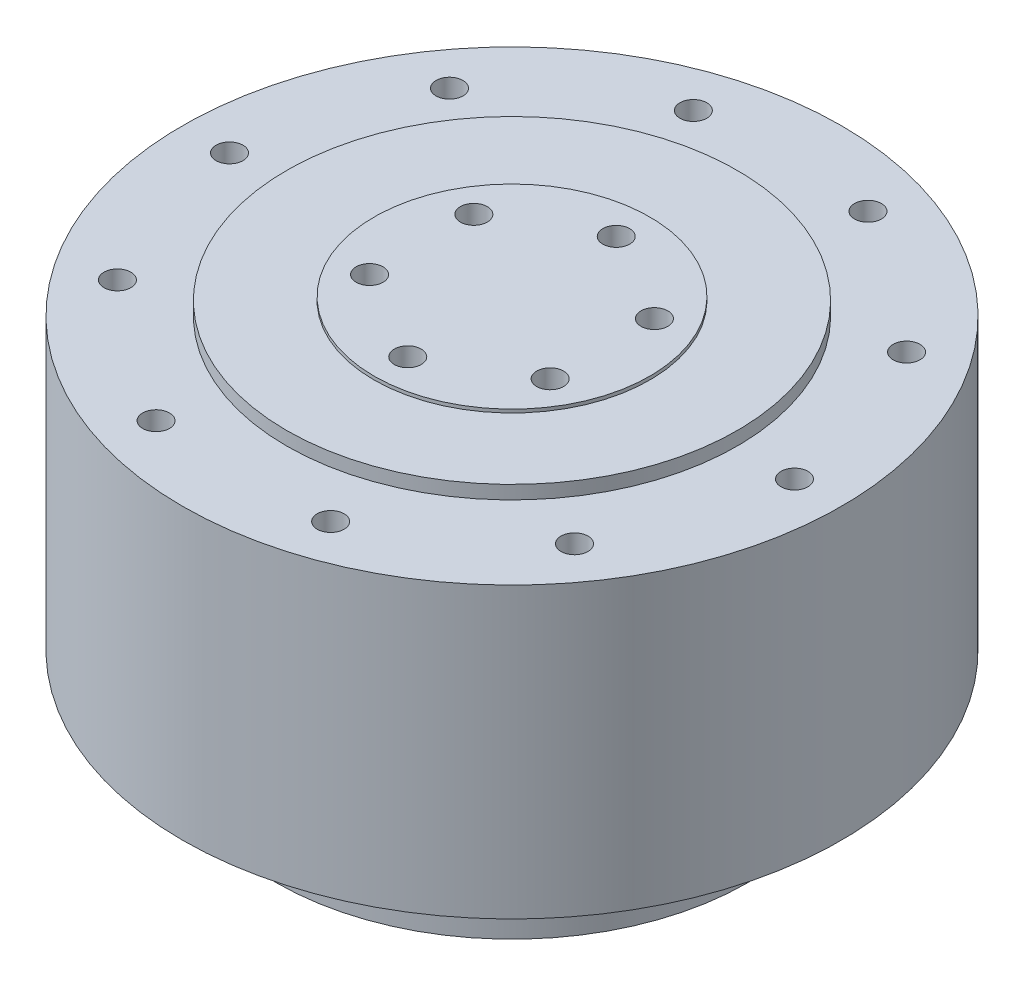
SolidWorks part; units mm, degrees
ref_plane "前基準面" through (0, 0, 0) normal (0, 0, 1) x (1, 0, 0)
ref_plane "上基準面" through (0, 0, 0) normal (0, 1, 0) x (1, 0, 0)
ref_plane "右基準面" through (0, 0, 0) normal (1, 0, 0) x (0, 0, -1)
sketch "草圖1" plane through (0, 0, 0) normal (0, 1, 0) x (1, 0, 0)
  circle A0 centre (0, 0) radius 49
  dimension "D1" = 98
extrude "填料-伸長1" add sketch "草圖1" along normal blind 43
sketch "草圖2" plane through (0, 43, 0) normal (0, 1, 0) x (1, 0, 0)
  circle A0 centre (0, 0) radius 33.5
  dimension "D1" = 67
extrude "填料-伸長2" add sketch "草圖2" along normal blind 2
sketch "草圖3" plane through (0, 0, 0) normal (0, -1, 0) x (1, 0, 0)
  line L0 (-16.6241, -30.8) -> (16.6241, -30.8)
  arc A0 (16.6241, -30.8) -> (-16.6241, -30.8) centre (0, 0) ccw
  point P5 (0, 35)
  point P6 (0, -30.8)
  dimension "D1" = 70
  dimension "D2" = 65.8
extrude "填料-伸長3" add sketch "草圖3" along normal blind 12.5
sketch "草圖4" plane through (0, 45, 0) normal (0, 1, 0) x (1, 0, 0)
  circle A0 centre (0, 0) radius 20.5
  dimension "D1" = 41
extrude "填料-伸長4" add sketch "草圖4" along normal blind 0.5
sketch "草圖5" plane through (0, 45.5, 0) normal (0, 1, 0) x (1, 0, 0)
  line L0 (0, 0) -> (50000, 0) construction
  line L1 (0, 0) -> (0, 50000) construction
  circle A1 centre (0, 15.5) radius 2
  dimension "D1" = 4
  dimension "D2" = 15.5
extrude "除料-伸長1" cut sketch "草圖5" against normal blind 5
pattern_circular "環狀複製排列1" count 6 over 360 about axis through (0, 0, 0) along (0, 1, 0) of "除料-伸長1"
sketch "草圖6" plane through (0, 43, 0) normal (0, 1, 0) x (1, 0, 0)
  line L0 (0, 0) -> (50000, 0) construction
  line L1 (0, 0) -> (0, 50000) construction
  circle A1 centre (-42, 0) radius 2
  dimension "D1" = 4
  dimension "D2" = 42
extrude "除料-伸長2" cut sketch "草圖6" against normal blind 5
pattern_circular "環狀複製排列2" count 10 over 360 about axis through (0, 0, 0) along (0, 1, 0) of "除料-伸長2"
sketch "草圖7" plane through (0, 0, 0) normal (0, -1, 0) x (1, 0, 0)
  line L0 (0, 0) -> (50000, 0) construction
  line L1 (0, 0) -> (0, 50000) construction
  circle A0 centre (42, 0) radius 2
  dimension "D1" = 4
  dimension "D2" = 42
extrude "除料-伸長3" cut sketch "草圖7" against normal blind 5
pattern_circular "環狀複製排列3" count 10 over 360 about axis through (0, 0, 0) along (0, 1, 0) of "除料-伸長3"
